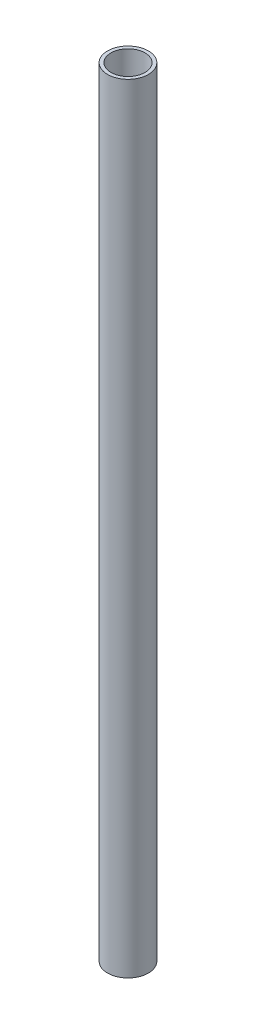
SolidWorks part; units mm, degrees
material "Thornel Mat VMA"
ref_plane "Front Plane" through (0, 0, 0) normal (0, 0, 1) x (1, 0, 0)
ref_plane "Top Plane" through (0, 0, 0) normal (0, 1, 0) x (1, 0, 0)
ref_plane "Right Plane" through (0, 0, 0) normal (1, 0, 0) x (0, 0, -1)
sketch "Sketch1" plane through (0, 0, 0) normal (0, 1, 0) x (1, 0, 0)
  circle A0 centre (0, 0) radius 8
  circle A1 centre (0, 0) radius 9.6
  dimension "D1" = 19.2
  dimension "D2" = 1.6
extrude "Boss-Extrude1" add sketch "Sketch1" along normal blind 366 contours A1 A0
